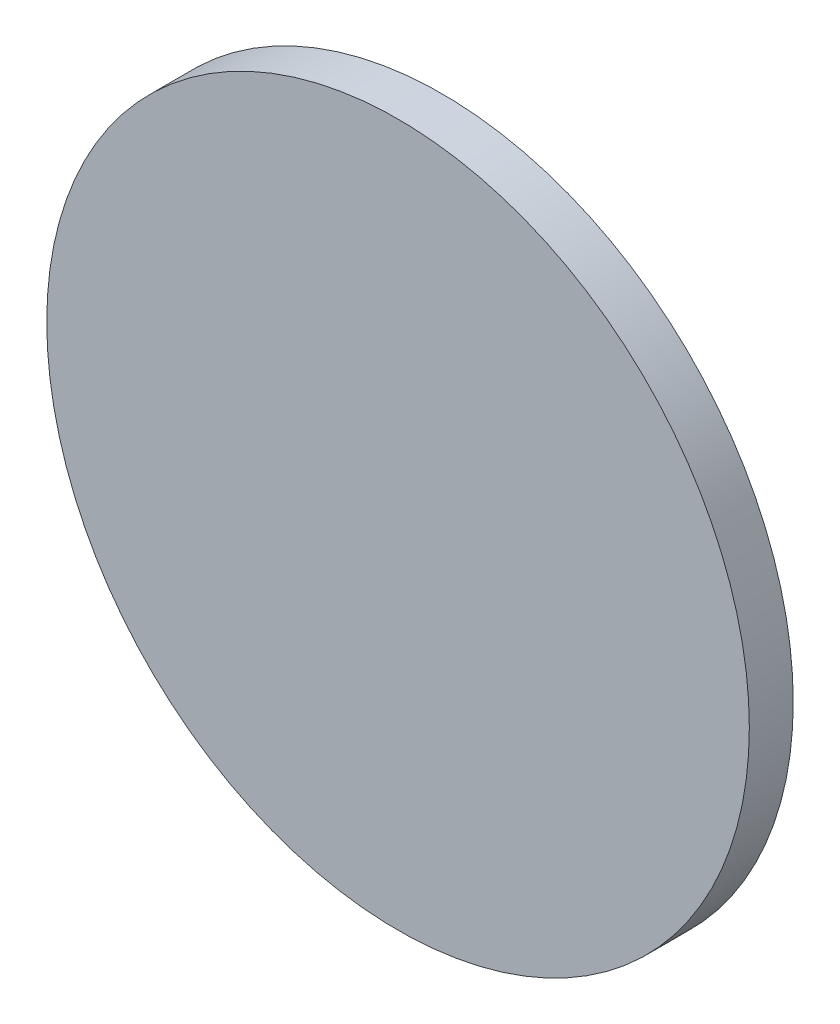
SolidWorks part; units mm, degrees
material "AISI 316 Stainless Steel Sheet (SS)"
ref_plane "Front Plane" through (0, 0, 0) normal (0, 0, 1) x (1, 0, 0)
ref_plane "Top Plane" through (0, 0, 0) normal (0, 1, 0) x (1, 0, 0)
ref_plane "Right Plane" through (0, 0, 0) normal (1, 0, 0) x (0, 0, -1)
sketch "Sketch1" plane through (0, 0, 0) normal (0, 0, 1) x (1, 0, 0)
  circle A0 centre (0, 0) radius 120
  dimension "D1" = 240
extrude "Boss-Extrude1" add sketch "Sketch1" along normal blind 15
